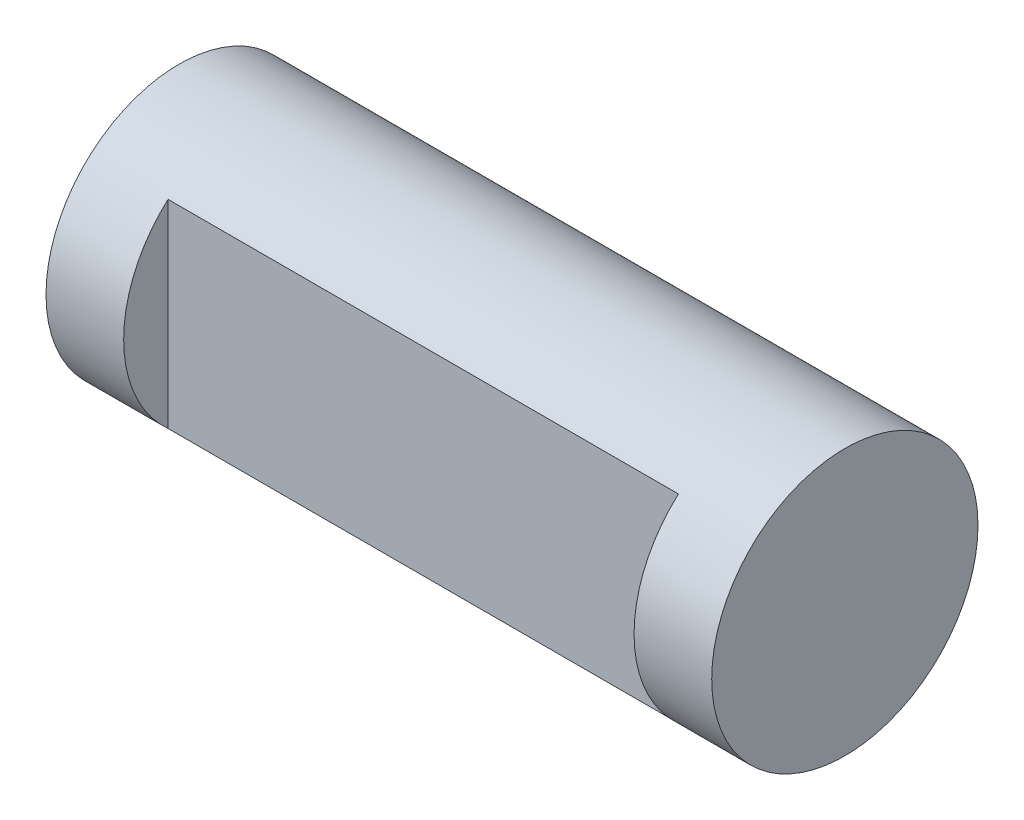
SolidWorks part; units mm, degrees
ref_plane "Спереди" through (0, 0, 0) normal (0, 0, 1) x (1, 0, 0)
ref_plane "Сверху" through (0, 0, 0) normal (0, 1, 0) x (1, 0, 0)
ref_plane "Справа" through (0, 0, 0) normal (1, 0, 0) x (0, 0, -1)
sketch "Эскиз1" plane through (0, 0, 0) normal (0, 0, 1) x (1, 0, 0)
  line L0 (0, 0) -> (60, 0)
  line L1 (60, 0) -> (60, 12)
  line L2 (60, 12) -> (0, 12)
  line L6 (0, 12) -> (0, 0)
  dimension "D1" = 12
  dimension "D2" = 60
revolve "Повернуть1" add sketch "Эскиз1" angle 360 about L0
ref_plane "Плоскость1" through (30, 0, 0) normal (-1, 0, 0) x (0, 0, 1)
sketch "Эскиз2" plane through (30, 0, 0) normal (-1, 0, 0) x (0, 0, 1)
  line L0 (8, 8.9443) -> (8, -8.9443)
  circle A0 centre (0, 0) radius 12 construction
  circle A1 centre (0, 0) radius 12
  dimension "D1" = 8
extrude "Вырез-Вытянуть2" cut sketch "Эскиз2" against normal offset from surface 7 and the other way offset from surface (23 mm away) 7 contours L0 A1
